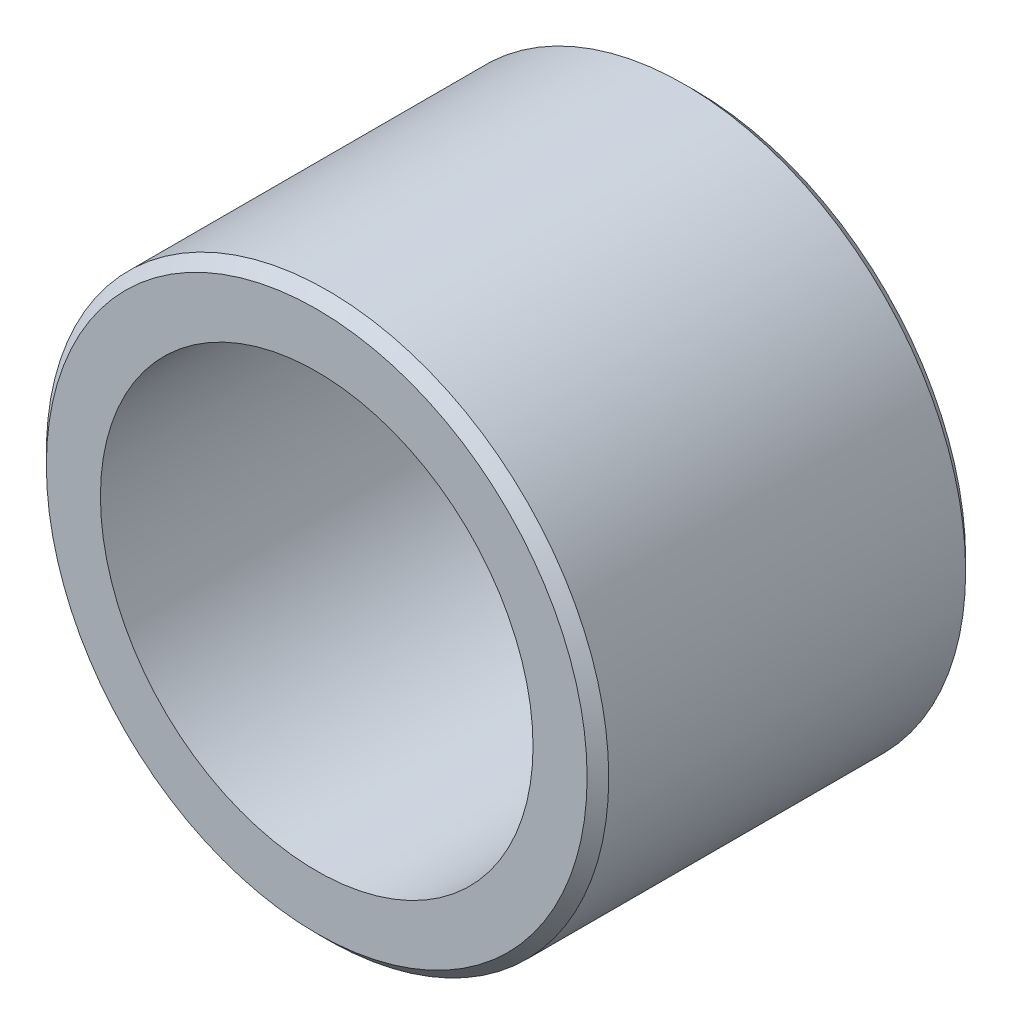
SolidWorks part; units mm, degrees
ref_plane "前视基准面" through (0, 0, 0) normal (0, 0, 1) x (1, 0, 0)
ref_plane "上视基准面" through (0, 0, 0) normal (0, 1, 0) x (1, 0, 0)
ref_plane "右视基准面" through (0, 0, 0) normal (1, 0, 0) x (0, 0, -1)
sketch "草图1" plane through (0, 0, 0) normal (0, 0, 1) x (1, 0, 0)
  circle A0 centre (0, 0) radius 13
  dimension "D1" = 26
extrude "凸台-拉伸1" add sketch "草图1" along normal blind 17.5
sketch "草图2" plane through (0, 0, 17.5) normal (0, 0, 1) x (1, 0, 0)
  circle A0 centre (0, 0) radius 10
  dimension "D1" = 20
extrude "切除-拉伸1" cut sketch "草图2" against normal blind 17.5
chamfer "倒角1" distance 0.5 angle 45 2 edges at (13, 0, 0) (13, 0, 17.5)
